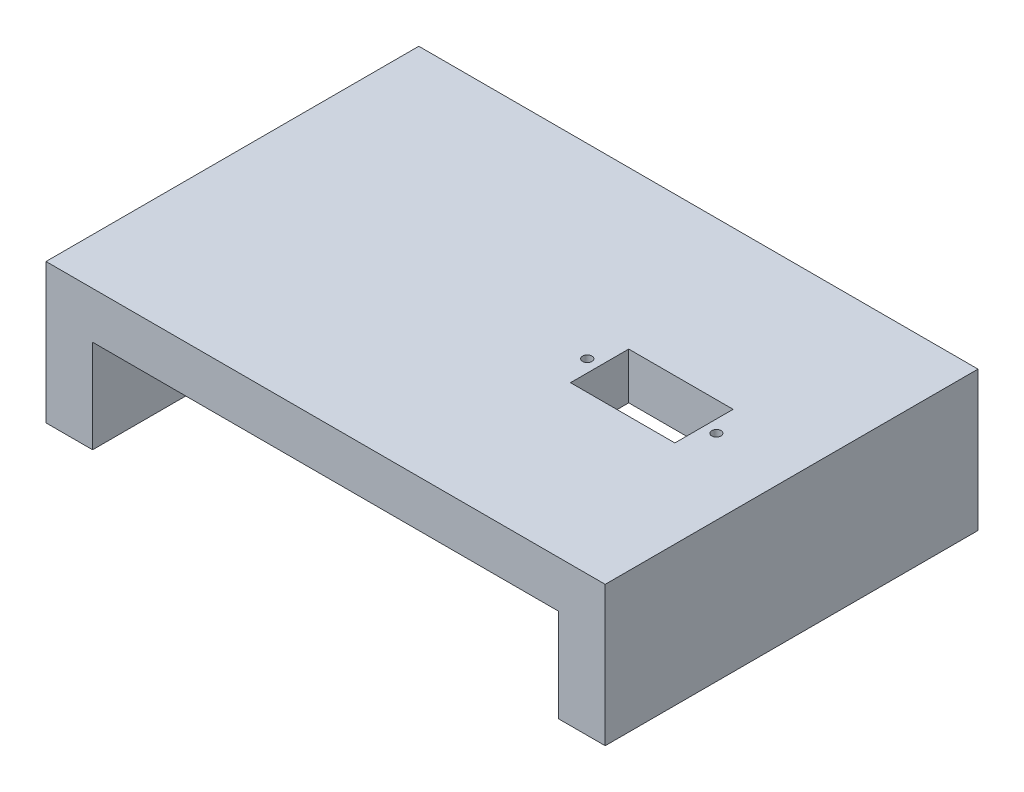
SolidWorks part; units mm, degrees
ref_plane "Front Plane" through (0, 0, 0) normal (0, 0, 1) x (1, 0, 0)
ref_plane "Top Plane" through (0, 0, 0) normal (0, 1, 0) x (1, 0, 0)
ref_plane "Right Plane" through (0, 0, 0) normal (1, 0, 0) x (0, 0, -1)
sketch "Sketch1" plane through (0, 0, 0) normal (0, 1, 0) x (1, 0, 0)
  line L1 (-60, -40) -> (60, -40)
  line L2 (-60, -40) -> (-60, 40)
  line L3 (-60, 40) -> (60, 40)
  line L4 (60, -40) -> (60, 40)
  line L5 (-60, -40) -> (60, 40) construction
  line L6 (-60, 40) -> (60, -40) construction
  point P0 (0, 0)
  dimension "D1" = 120
  dimension "D2" = 80
extrude "Boss-Extrude1" add sketch "Sketch1" along normal blind 10
sketch "Sketch2" plane through (0, 10, 0) normal (0, 1, 0) x (1, 0, 0)
  line L0 (0, 0) -> (60, 0) construction
  line L1 (60, -40) -> (60, 40) construction
  line L2 (30, -40) -> (30, 40) construction
  line L3 (60, 40) -> (-60, 40) construction
  line L5 (18.8, -6.25) -> (41.2, -6.25)
  line L6 (18.8, -6.25) -> (18.8, 6.25)
  line L7 (18.8, 6.25) -> (41.2, 6.25)
  line L8 (41.2, -6.25) -> (41.2, 6.25)
  line L9 (18.8, -6.25) -> (41.2, 6.25) construction
  line L10 (18.8, 6.25) -> (41.2, -6.25) construction
  point P4 (30, 0)
  point P10 (30, 0)
  dimension "D1" = 22.4
  dimension "D2" = 12.5
extrude "Cut-Extrude1" cut sketch "Sketch2" against normal blind 10
sketch "Sketch3" plane through (0, 0, 0) normal (0, -1, 0) x (1, 0, 0)
  line L0 (60, -40) -> (-60, -40) construction
  line L1 (-60, 40) -> (-50, 40)
  line L2 (-60, 40) -> (-60, -40)
  line L3 (-60, -40) -> (-50, -40)
  line L4 (-50, 40) -> (-50, -40)
  line L5 (-60, 40) -> (-50, -40) construction
  line L6 (-60, -40) -> (-50, 40) construction
  line L8 (60, 40) -> (50, 40)
  line L9 (60, 40) -> (60, -40)
  line L10 (60, -40) -> (50, -40)
  line L11 (50, 40) -> (50, -40)
  line L12 (60, 40) -> (50, -40) construction
  line L13 (60, -40) -> (50, 40) construction
  point P4 (-55, 0)
  point P12 (55, 0)
  dimension "D1" = 10
  dimension "D2" = 10
extrude "Boss-Extrude2" add sketch "Sketch3" along normal blind 20
sketch "Sketch4" plane through (0, 10, 0) normal (0, 1, 0) x (1, 0, 0)
  line L0 (13.8, 0) -> (41.2, 0) construction
  line L1 (16.15, 0) -> (43.85, 0) construction
  line L2 (41.2, -6.25) -> (41.2, 6.25) construction
  line L3 (30, 6.25) -> (30, -6.25)
  line L4 (41.2, 6.25) -> (18.8, 6.25) construction
  line L5 (18.8, -6.25) -> (41.2, -6.25) construction
  circle A0 centre (16.15, 0) radius 1
  circle A1 centre (43.85, 0) radius 1
  point P16 (30, 0)
  dimension "D1" = 27.7
extrude "Cut-Extrude3" cut sketch "Sketch4" against normal blind 12 contours A0 | A1
